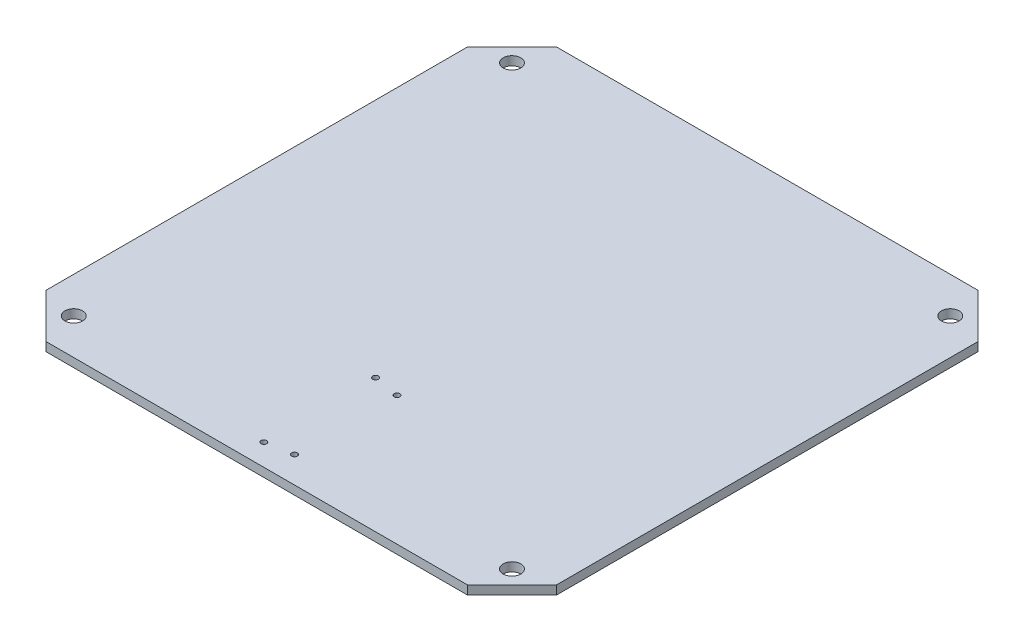
SolidWorks part; units mm, degrees
material "ABS"
ref_plane "Front Plane" through (0, 0, 0) normal (0, 0, 1) x (1, 0, 0)
ref_plane "Top Plane" through (0, 0, 0) normal (0, 1, 0) x (1, 0, 0)
ref_plane "Right Plane" through (0, 0, 0) normal (1, 0, 0) x (0, 0, -1)
sketch "Sketch1" plane through (0, 0, 0) normal (0, 1, 0) x (1, 0, 0)
  line L0 (-38, 46) -> (-46, 38)
  line L1 (-38, -46) -> (38, -46)
  line L2 (-46, -38) -> (-46, 38)
  line L3 (-38, 46) -> (38, 46)
  line L4 (46, -38) -> (46, 38)
  line L5 (-42, -42) -> (42, 42) construction
  line L6 (-42, 42) -> (42, -42) construction
  line L7 (38, 46) -> (46, 38)
  line L8 (46, -38) -> (38, -46)
  line L9 (-38, -46) -> (-46, -38)
  point P0 (0, 0)
  dimension "D1" = 92
  dimension "D2" = 92
  dimension "D3" = 8
  dimension "D4" = 8
  dimension "D5" = 8
  dimension "D6" = 8
  dimension "D7" = 8
  dimension "D8" = 8
  dimension "D9" = 8
  dimension "D10" = 8
  dimension "D11" = 46
  dimension "D12" = 46
  dimension "D13" = 90
extrude "Boss-Extrude1" add sketch "Sketch1" along normal blind 1.59 contours L2 L0 L3 L7 L4 L8 L1 L9
sketch "Sketch3" plane through (0, 1.59, 0) normal (0, 1, 0) x (1, 0, 0)
  line L1 (-47.5, -47.5) -> (47.5, -47.5) construction
  line L2 (-47.5, -47.5) -> (-47.5, 47.5) construction
  line L3 (-47.5, 47.5) -> (47.5, 47.5) construction
  line L4 (47.5, -47.5) -> (47.5, 47.5) construction
  line L5 (-47.5, -47.5) -> (47.5, 47.5) construction
  line L6 (-47.5, 47.5) -> (47.5, -47.5) construction
  circle A0 centre (-39.5, 39.5) radius 1.59
  circle A1 centre (39.5, 39.5) radius 1.59
  circle A2 centre (39.5, -39.5) radius 1.59
  circle A3 centre (-39.5, -39.5) radius 1.59
  circle A4 centre (-2.67, -21.93) radius 0.51
  circle A5 centre (2.03, -22.75) radius 0.51
  circle A6 centre (-2.67, -42.07) radius 0.51
  circle A7 centre (2.03, -41.24) radius 0.51
  point P0 (0, 0)
  point P22 (0, 0)
  point P23 (0, 0)
  point P24 (0, 0)
  dimension "D3" = 3.18
  dimension "D8" = 1.02
  dimension "D1" = 95
  dimension "D2" = 95
  dimension "D4" = 8
  dimension "D5" = 8
  dimension "D6" = 8
  dimension "D7" = 8
  dimension "D9" = 5.43
  dimension "D10" = 6.26
  dimension "D11" = 25.57
  dimension "D12" = 24.75
  dimension "D13" = 44.83
  dimension "D14" = 49.53
extrude "Cut-Extrude1" cut sketch "Sketch3" against normal through all
